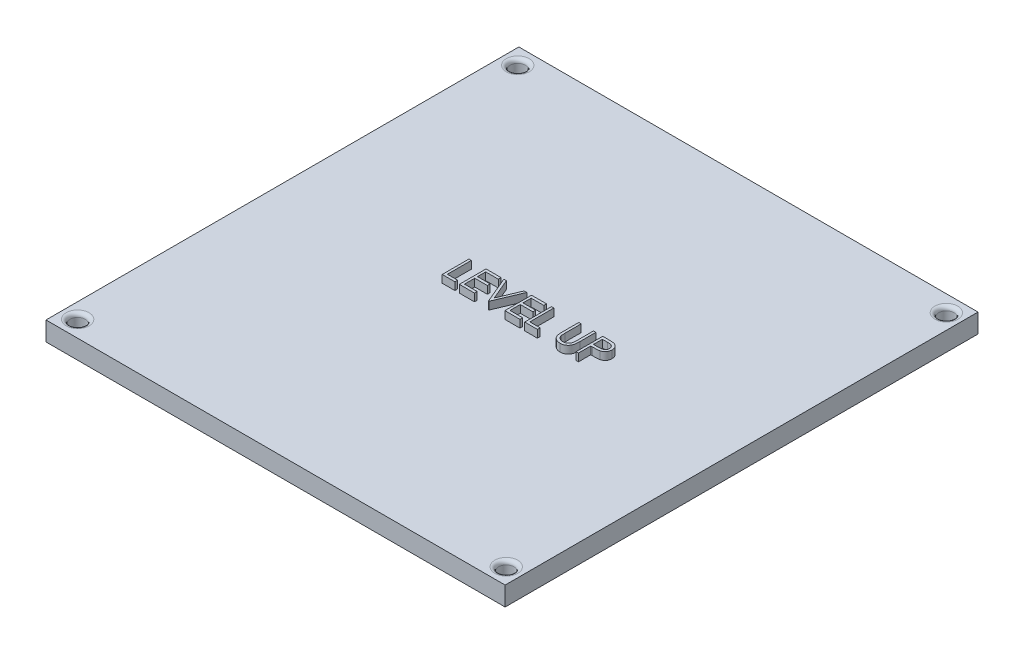
SolidWorks part; units mm, degrees
ref_plane "Front Plane" through (0, 0, 0) normal (0, 0, 1) x (1, 0, 0)
ref_plane "Top Plane" through (0, 0, 0) normal (0, 1, 0) x (1, 0, 0)
ref_plane "Right Plane" through (0, 0, 0) normal (1, 0, 0) x (0, 0, -1)
sketch "Sketch1" plane through (0, 0, 0) normal (0, 1, 0) x (1, 0, 0)
  line L1 (-30.1, 31) -> (30.1, 31)
  line L2 (-30.1, 31) -> (-30.1, -31)
  line L3 (-30.1, -31) -> (30.1, -31)
  line L4 (30.1, 31) -> (30.1, -31)
  line L5 (-30.1, 31) -> (30.1, -31) construction
  line L6 (-30.1, -31) -> (30.1, 31) construction
  point P1 (0, 0)
  dimension "D1" = 60.2
  dimension "D2" = 62
extrude "Boss-Extrude1" add sketch "Sketch1" along normal blind 2.5
sketch "Sketch2" plane through (0, 2.5, 0) normal (0, 1, 0) x (1, 0, 0)
  circle A0 centre (-28.1, 28.85) radius 1
  circle A1 centre (28.1, 28.85) radius 1
  circle A2 centre (28.1, -28.85) radius 1
  circle A3 centre (-28.1, -28.85) radius 1
extrude "Cut-Extrude2" cut sketch "Sketch2" against normal blind 2.5
fillet "Fillet3" radius 0.5 4 edges at (-28.1, 2.5, 27.85) (28.1, 2.5, 29.85) (28.1, 2.5, -29.85) (-28.1, 2.5, -27.85)
sketch "Sketch3" plane through (0, 2.5, 0) normal (0, 1, 0) x (1, 0, 0)
  text T0 "LEVEL UP"
extrude "Boss-Extrude2" add sketch "Sketch3" along normal blind 1
